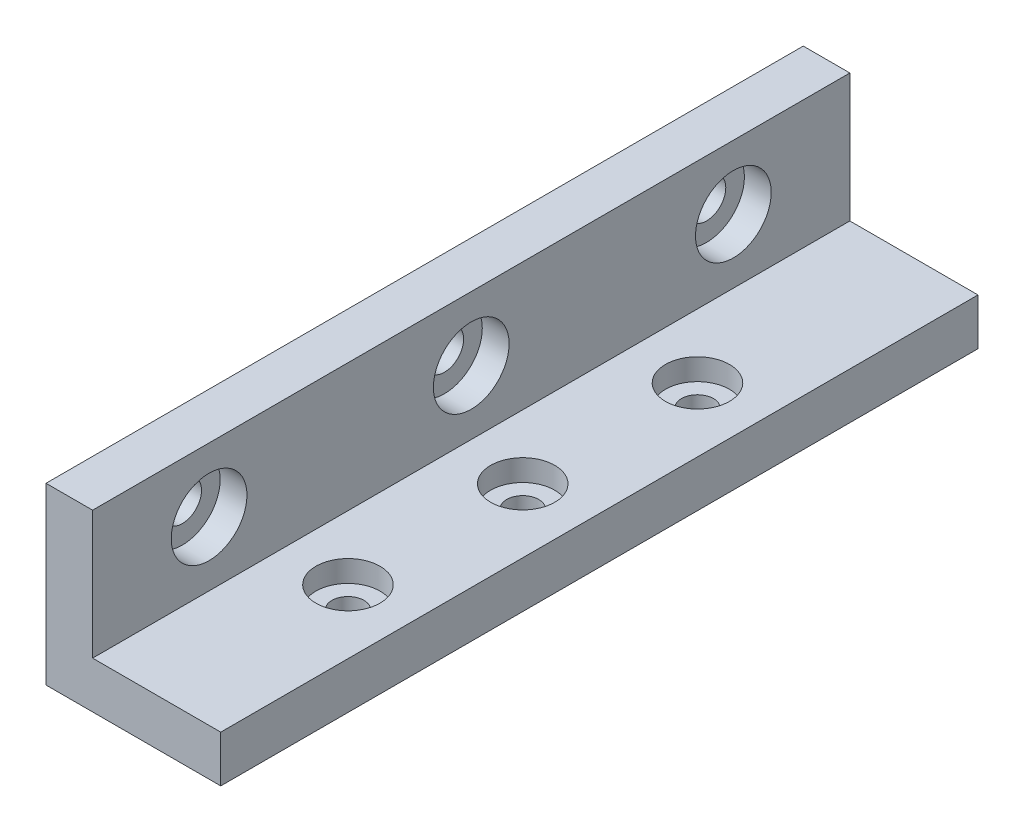
SolidWorks part; units mm, degrees
ref_plane "Front Plane" through (0, 0, 0) normal (0, 0, 1) x (1, 0, 0)
ref_plane "Top Plane" through (0, 0, 0) normal (0, 1, 0) x (1, 0, 0)
ref_plane "Right Plane" through (0, 0, 0) normal (1, 0, 0) x (0, 0, -1)
sketch "Sketch1" plane through (0, 0, 0) normal (0, 0, 1) x (1, 0, 0)
  line L1 (0, 0) -> (8, 0)
  line L2 (0, 0) -> (0, 30)
  line L3 (0, 30) -> (8, 30)
  line L4 (8, 8) -> (8, 30)
  line L5 (0, 0) -> (30, 0)
  line L6 (0, 0) -> (0, 8)
  line L7 (8, 8) -> (30, 8)
  line L8 (30, 0) -> (30, 8)
  dimension "D1" = 30
  dimension "D2" = 30
  dimension "D3" = 8
  dimension "D4" = 8
extrude "Boss-Extrude1" add sketch "Sketch1" along normal blind 130 contours L5 L8 L7 L4 L3 L2 L1
hole_wizard "CBORE for M5 Pan Head Screw1" positions "Sketch3" profile "Sketch2" counterbore size "M5" standard "ISO" end condition through all
sketch "Sketch3" plane through (0, 8, 0) normal (0, 1, 0) x (1, 0, 0)
  line L0 (30, -130) -> (30, 0) construction
  line L2 (8, -130) -> (8, 0) construction
  point P0 (19, -67.1605)
  point P2 (19, -37.1605)
  point P4 (19, -97.1605)
  point P13 (15.1244, -65.9189)
  dimension "D1" = 11
  dimension "D2" = 11
  dimension "D3" = 11
  dimension "D4" = 30
  dimension "D5" = 30
sketch "Sketch2" plane through (19, 8, 67.1605) normal (1, 0, 0) x (0, 0, 1)
  line L0 (0, 0) -> (0, 8)
  line L1 (0, 8) -> (2.75, 8)
  line L3 (2.75, 8) -> (2.75, 3.7)
  line L4 (2.75, 3.7) -> (5.5, 3.7)
  line L5 (5.5, 3.7) -> (5.5, 0)
  line L7 (5.5, 0) -> (0, 0)
  line L11 (0, -6.35) -> (0, 107.95) construction
  dimension "Thru Hole Dia." = 5.5
  dimension "Thru Hole Depth" = 8
  dimension "C'Bore Dia." = 11
  dimension "C'Bore Depth" = 3.7
hole_wizard "CBORE for M6 Pan Head Screw1" positions "Sketch5" profile "Sketch4" counterbore size "M6" standard "ISO" end condition through all
sketch "Sketch5" plane through (8, 0, 0) normal (1, 0, 0) x (0, 0, -1)
  line L0 (-130, 8) -> (-130, 30) construction
  line L2 (-130, 30) -> (0, 30) construction
  point P0 (-110, 19)
  point P2 (-65, 19)
  point P4 (-20, 19)
  dimension "D1" = 45
  dimension "D2" = 45
  dimension "D3" = 65
  dimension "D4" = 11
sketch "Sketch4" plane through (8, 19, 110) normal (0, 1, 0) x (0, 0, -1)
  line L0 (0, 0) -> (0, 8)
  line L1 (0, 8) -> (3.3, 8)
  line L3 (3.3, 8) -> (3.3, 4.6)
  line L4 (3.3, 4.6) -> (6.5, 4.6)
  line L5 (6.5, 4.6) -> (6.5, 0)
  line L7 (6.5, 0) -> (0, 0)
  line L11 (0, -6.35) -> (0, 107.95) construction
  dimension "Thru Hole Dia." = 6.6
  dimension "Thru Hole Depth" = 8
  dimension "C'Bore Dia." = 13
  dimension "C'Bore Depth" = 4.6
